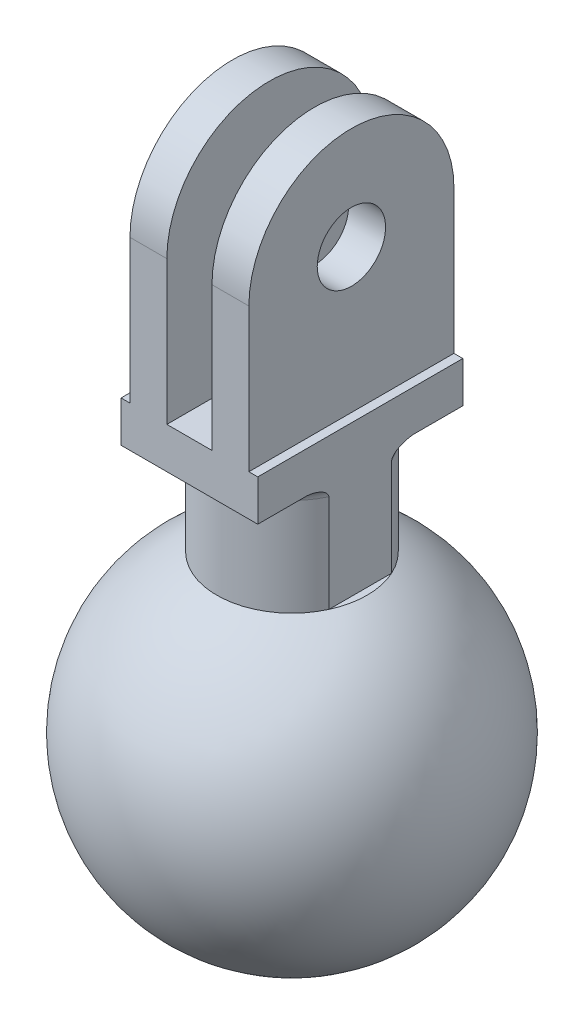
SolidWorks part; units mm, degrees
ref_plane "Front Plane" through (0, 0, 0) normal (0, 0, 1) x (1, 0, 0)
ref_plane "Top Plane" through (0, 0, 0) normal (0, 1, 0) x (1, 0, 0)
ref_plane "Right Plane" through (0, 0, 0) normal (1, 0, 0) x (0, 0, -1)
sketch "Sketch1" plane through (0, 0, 0) normal (0, 0, 1) x (1, 0, 0)
  line L0 (0, 0) -> (5.5, 0)
  line L1 (5.5, 0) -> (5.5, -8)
  line L2 (0, 0) -> (0, -36.9552)
  line L3 (5.5, 0) -> (6.5, 0)
  arc A0 (5.5, -8) -> (0, -32.1473) centre (0, -19.4473) cw
  arc A1 (6.5, 0) -> (5.5, -0.8617) centre (6.4309, -0.9309) ccw
  dimension "D1" = 12.7
  dimension "D2" = 5.5
  dimension "D3" = 8
  dimension "D4" = 1
revolve "Revolve1" add sketch "Sketch1" angle 360 about L2
sketch "Sketch2" plane through (0, 0, 0) normal (0, 1, 0) x (1, 0, 0)
  line L1 (5, -7.5) -> (-5, -7.5)
  line L2 (5, -7.5) -> (5, 7.5)
  line L3 (5, 7.5) -> (-5, 7.5)
  line L4 (-5, -7.5) -> (-5, 7.5)
  line L5 (5, -7.5) -> (-5, 7.5) construction
  line L6 (5, 7.5) -> (-5, -7.5) construction
  point P0 (0, 0)
  dimension "D1" = 15
  dimension "D2" = 10
extrude "Boss-Extrude1" add sketch "Sketch2" along normal blind 3
sketch "Sketch3" plane through (0, 3, 0) normal (0, 1, 0) x (1, 0, 0)
  line L0 (0, 0) -> (0, 1.7203)
  line L1 (-1.65, -7.5) -> (-4.35, -7.5)
  line L2 (-1.65, -7.5) -> (-1.65, 7.5)
  line L3 (-1.65, 7.5) -> (-4.35, 7.5)
  line L4 (-4.35, -7.5) -> (-4.35, 7.5)
  line L5 (-1.65, -7.5) -> (-4.35, 7.5) construction
  line L6 (-1.65, 7.5) -> (-4.35, -7.5) construction
  line L7 (1.65, 7.5) -> (4.35, 7.5)
  line L8 (4.35, -7.5) -> (4.35, 7.5)
  line L9 (1.65, -7.5) -> (4.35, -7.5)
  line L10 (1.65, -7.5) -> (1.65, 7.5)
  point P0 (-3, 0)
  point P5 (-1.65, 0)
  line M11 (-5, -7.5) -> (5, -7.5)
  line M13 (5, 7.5) -> (-5, 7.5)
  dimension "D1" = 2.7
  dimension "D2" = 1.65
  dimension "D3" = 15
extrude "Boss-Extrude2" add sketch "Sketch3" along normal blind 18 contours L4 L2 M11 M13 | L10 L8 M11 M13
sketch "Sketch4" plane through (-4.35, 0, 0) normal (-1, 0, 0) x (0, 0, 1)
  line L0 (-7.5, 13.5) -> (-7.5, 21)
  line L1 (-7.5, 21) -> (0, 21)
  line L2 (7.5, 21) -> (-7.5, 21) construction
  line L3 (0, 21) -> (7.5, 21)
  line L4 (7.5, 21) -> (7.5, 13.5)
  circle A0 centre (0, 13.5) radius 7.5
  circle A1 centre (0, 13.5) radius 2.5
  line M2 (7.5, 3) -> (7.5, 21)
  line M3 (7.5, 21) -> (-7.5, 21)
  line M4 (-7.5, 21) -> (-7.5, 3)
  dimension "D2" = 5
  dimension "D1" = 13.5
extrude "Cut-Extrude1" cut sketch "Sketch4" against normal through all contours A1 | A0 M3 M4 | A0 M2 M3
sketch "Sketch5" plane through (0, 3, 0) normal (0, 1, 0) x (1, 0, 0)
  line L1 (5, 7.5) -> (8.2671, 7.5)
  line L2 (5, 7.5) -> (5, -5.5554)
  line L3 (5, -5.5554) -> (8.2671, -5.5554)
  line L4 (8.2671, 7.5) -> (8.2671, -5.5554)
  line L5 (-5, 7.5) -> (-7.3996, 7.5)
  line L6 (-5, 7.5) -> (-5, -4.942)
  line L7 (-5, -4.942) -> (-7.3996, -4.942)
  line L8 (-7.3996, 7.5) -> (-7.3996, -4.942)
extrude "Cut-Extrude2" cut sketch "Sketch5" against normal blind 11
